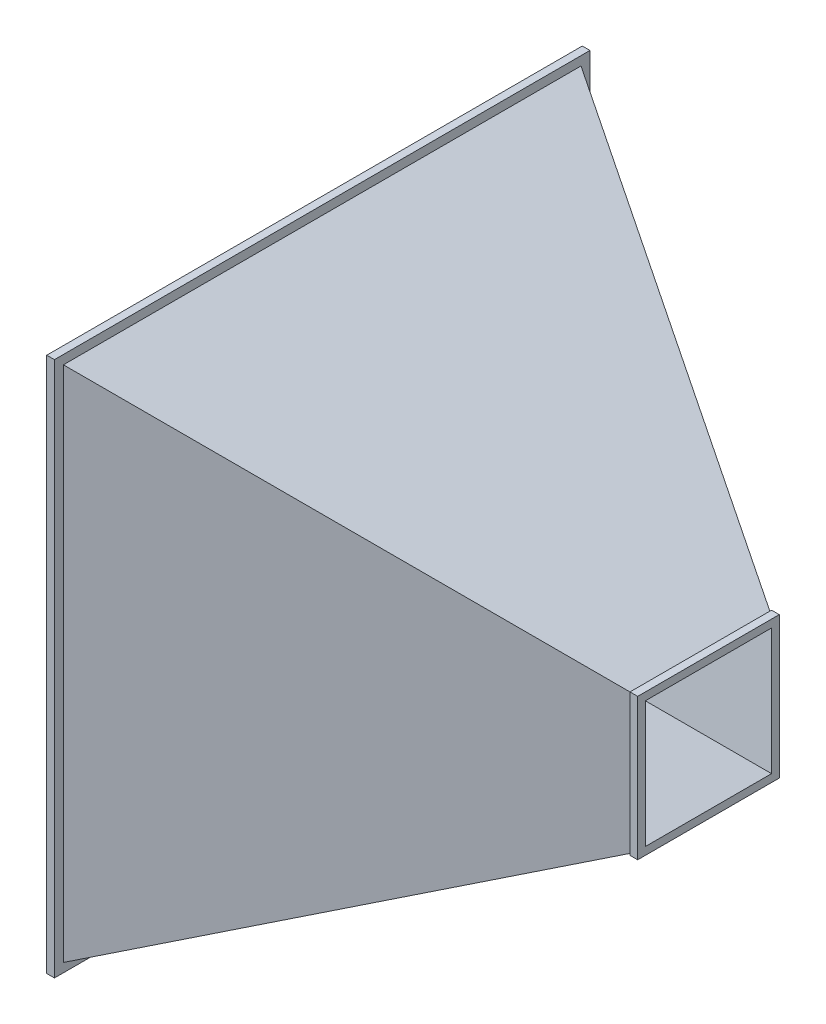
SolidWorks part; units mm, degrees
ref_plane "Front Plane" through (0, 0, 0) normal (0, 0, 1) x (1, 0, 0)
ref_plane "Top Plane" through (0, 0, 0) normal (0, 1, 0) x (1, 0, 0)
ref_plane "Right Plane" through (0, 0, 0) normal (1, 0, 0) x (0, 0, -1)
sketch "Sketch1" plane through (0, 0, 0) normal (1, 0, 0) x (0, 0, -1)
  line L1 (-512, -512) -> (512, -512)
  line L2 (-512, -512) -> (-512, 512)
  line L3 (-512, 512) -> (512, 512)
  line L4 (512, -512) -> (512, 512)
  line L5 (-512, -512) -> (512, 512) construction
  line L6 (-512, 512) -> (512, -512) construction
  point P0 (0, 0)
  dimension "D1" = 1024
  dimension "D2" = 1024
ref_plane "Plane1" through (768, 0, 0) normal (1, 0, 0) x (0, 0, -1)
sketch "Sketch2" plane through (768, 0, 0) normal (1, 0, 0) x (0, 0, -1)
  line L1 (-128, 128) -> (128, 128)
  line L2 (-128, 128) -> (-128, -128)
  line L3 (-128, -128) -> (128, -128)
  line L4 (128, 128) -> (128, -128)
  line L5 (-128, 128) -> (128, -128) construction
  line L6 (-128, -128) -> (128, 128) construction
  point P0 (0, 0)
  dimension "D1" = 256
  dimension "D2" = 256
loft "Loft3" add profiles "Sketch1", "Sketch2"
sketch "Sketch3" plane through (768, 0, 0) normal (1, 0, 0) x (0, 0, -1)
  line L0 (-512, 512) -> (512, -512) construction
  line L1 (-123, 123) -> (123, 123)
  line L2 (-123, 123) -> (-123, -123)
  line L3 (-123, -123) -> (123, -123)
  line L4 (123, 123) -> (123, -123)
  line L5 (-123, 123) -> (123, -123) construction
  line L6 (-123, -123) -> (123, 123) construction
  line L7 (128, -128) -> (128, 128) construction
  point P0 (0, 0)
  dimension "D1" = 5
sketch "Sketch11" plane through (768, 0, 0) normal (1, 0, 0) x (0, 0, -1)
  line L8 (138, -138) -> (138, 138)
  line L9 (138, 138) -> (-138, 138)
  line L10 (-138, 138) -> (-138, -138)
  line L11 (-138, -138) -> (138, -138)
  line L12 (138, -138) -> (138, 138)
  line L13 (138, 138) -> (-138, 138)
  line L14 (-138, 138) -> (-138, -138)
  line L15 (-138, -138) -> (138, -138)
  dimension "D1" = 10
sketch "Sketch12" plane through (0, 0, 0) normal (-1, 0, 0) x (0, 0, 1)
  line L8 (-522, 522) -> (-522, -522)
  line L9 (-522, -522) -> (522, -522)
  line L10 (522, -522) -> (522, 522)
  line L11 (522, 522) -> (-522, 522)
  line L12 (-522, 522) -> (-522, -522)
  line L13 (-522, -522) -> (522, -522)
  line L14 (522, -522) -> (522, 522)
  line L15 (522, 522) -> (-522, 522)
  dimension "D1" = 10
extrude "Boss-Extrude7" add sketch "Sketch11" against normal blind 15
extrude "Boss-Extrude8" add sketch "Sketch12" against normal blind 15
sketch "Sketch10" plane through (0, 0, 0) normal (1, 0, 0) x (0, 0, -1)
  line L8 (517, 517) -> (-517, 517)
  line L16 (517, 517) -> (-517, 517)
  line L20 (517, -517) -> (517, 517)
  line L22 (517, -517) -> (517, 517)
  line L24 (-517, -517) -> (517, -517)
  line L25 (-517, -517) -> (517, -517)
  line L26 (-517, 517) -> (-517, -517)
  line L27 (-517, 517) -> (-517, -517)
  dimension "D1" = 5
sketch "Sketch13" plane through (0, 0, 0) normal (-1, 0, 0) x (0, 0, 1)
  line L0 (522, -522) -> (522, 522) construction
  line L1 (-512, 512) -> (512, 512)
  line L2 (-512, 512) -> (-512, -512)
  line L3 (-512, -512) -> (512, -512)
  line L4 (512, 512) -> (512, -512)
  line L5 (-512, 512) -> (512, -512) construction
  line L6 (-512, -512) -> (512, 512) construction
  line L7 (-522, -522) -> (522, -522) construction
  point P0 (0, 0)
  dimension "D1" = 10
  dimension "D2" = 10
loft "Cut-Loft4" cut profiles "Sketch13", "Sketch3"
